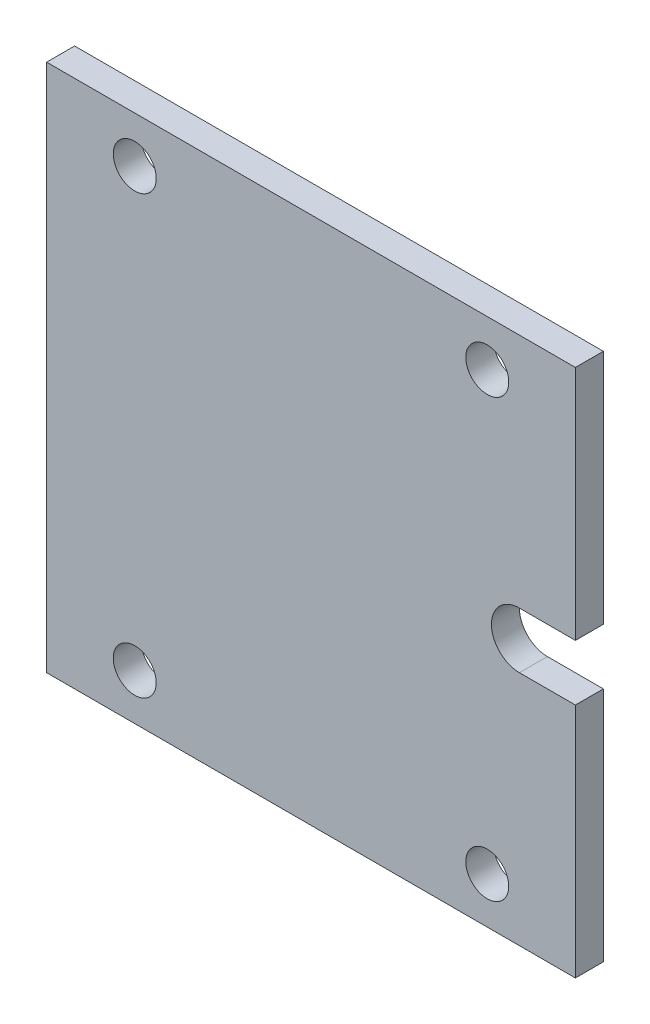
SolidWorks part; units mm, degrees
material "6061-T6 (SS)"
ref_plane "Front Plane" through (0, 0, 0) normal (0, 0, 1) x (1, 0, 0)
ref_plane "Top Plane" through (0, 0, 0) normal (0, 1, 0) x (1, 0, 0)
ref_plane "Right Plane" through (0, 0, 0) normal (1, 0, 0) x (0, 0, -1)
sketch "Sketch2" plane through (0, 0, 0) normal (0, 0, 1) x (1, 0, 0)
  line L1 (-10, -12.389) -> (10, -12.389) construction
  line L2 (-10, -12.389) -> (-10, 12.3891) construction
  line L3 (-10, 12.3891) -> (10, 12.3891) construction
  line L4 (10, -12.389) -> (10, 12.3891) construction
  line L5 (-10, -12.389) -> (10, 12.3891) construction
  line L6 (-10, 12.3891) -> (10, -12.389) construction
  line L7 (-15, -15) -> (15, -15)
  line L8 (-15, -15) -> (-15, 15)
  line L9 (-15, 15) -> (15, 15)
  line L10 (15, -15) -> (15, 15)
  line L11 (-15, -15) -> (15, 15) construction
  line L12 (-15, 15) -> (15, -15) construction
  circle A0 centre (-10, 12.3891) radius 1.2192
  circle A1 centre (10, 12.3891) radius 1.2192
  circle A2 centre (10, -12.389) radius 1.2192
  circle A3 centre (-10, -12.389) radius 1.2192
  point P0 (0, 0)
  point P10 (0, 0)
  dimension "D3" = 2.4384
  dimension "D1" = 20
  dimension "D2" = 24.7781
  dimension "D4" = 30
  dimension "D5" = 30
extrude "Boss-Extrude1" add sketch "Sketch2" along normal blind 1.5875
sketch "Sketch3" plane through (0, 0, 0) normal (0, 0, -1) x (-1, 0, 0)
  line L0 (-15, -15) -> (-15, 15) construction
  line L1 (-11.825, -1.5875) -> (-15, -1.5875)
  line L2 (-15, -1.5875) -> (-15, 1.5875)
  line L3 (-15, 1.5875) -> (-11.825, 1.5875)
  arc A0 (-11.825, -1.5875) -> (-11.825, 1.5875) centre (-11.825, 0) ccw
  dimension "D2" = 3.175
  dimension "D1" = 3.175
extrude "Cut-Extrude1" cut sketch "Sketch3" against normal through all
